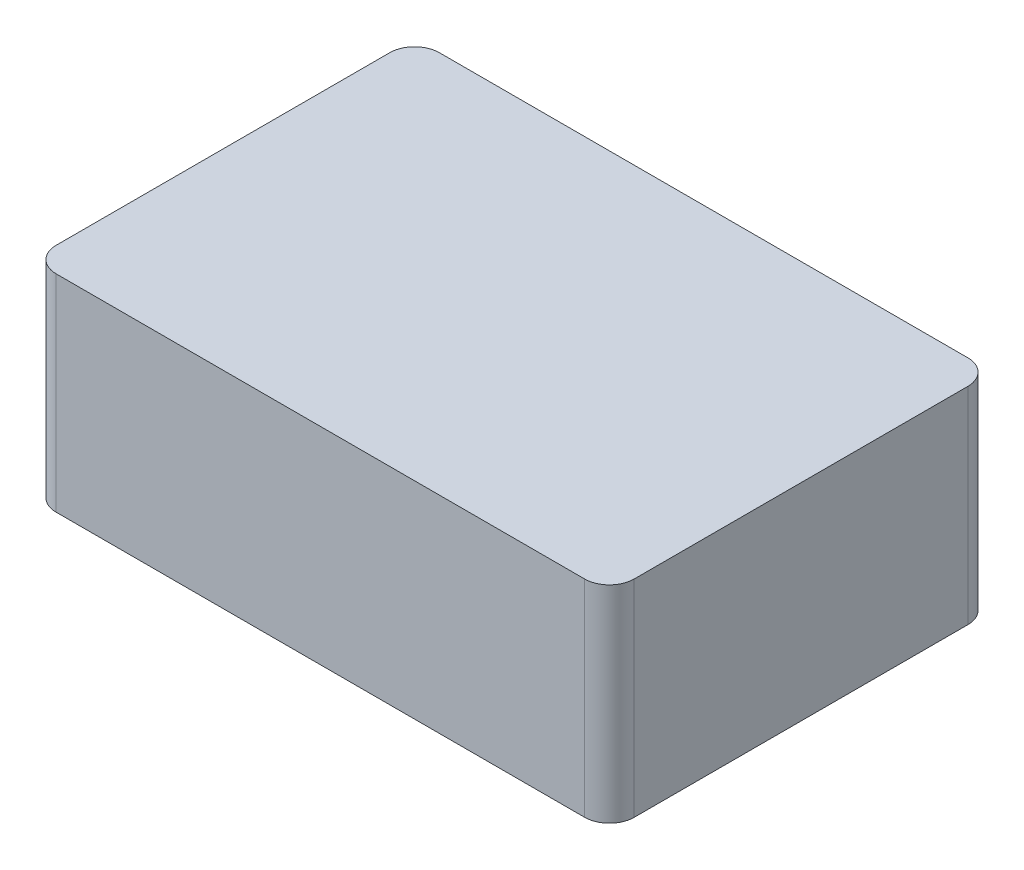
SolidWorks part; units mm, degrees
ref_plane "Front Plane" through (0, 0, 0) normal (0, 0, 1) x (1, 0, 0)
ref_plane "Top Plane" through (0, 0, 0) normal (0, 1, 0) x (1, 0, 0)
ref_plane "Right Plane" through (0, 0, 0) normal (1, 0, 0) x (0, 0, -1)
sketch "Sketch1" plane through (0, 0, 0) normal (0, 1, 0) x (1, 0, 0)
  line L1 (-35, -23.2) -> (35, -23.2)
  line L2 (-35, -23.2) -> (-35, 23.2)
  line L3 (-35, 23.2) -> (35, 23.2)
  line L4 (35, -23.2) -> (35, 23.2)
  line L5 (-35, -23.2) -> (35, 23.2) construction
  line L6 (-35, 23.2) -> (35, -23.2) construction
  point P0 (0, 0)
  dimension "D1" = 70
  dimension "D2" = 46.4
extrude "Boss-Extrude1" add sketch "Sketch1" along normal blind 25
fillet "Fillet1" radius 3 4 edges at (35, 12.5, -23.2) (-35, 12.5, -23.2) (-35, 12.5, 23.2) (35, 12.5, 23.2)
